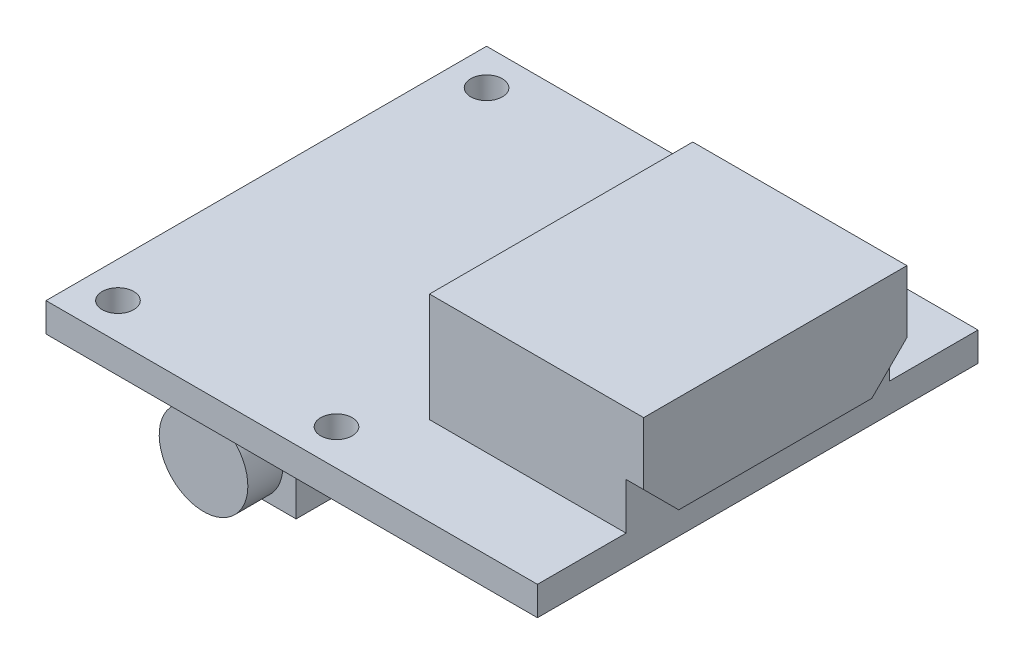
SolidWorks part; units mm, degrees
ref_plane "Front" through (0, 0, 0) normal (0, 0, 1) x (1, 0, 0)
ref_plane "Top" through (0, 0, 0) normal (0, 1, 0) x (1, 0, 0)
ref_plane "Right" through (0, 0, 0) normal (1, 0, 0) x (0, 0, -1)
sketch "Sketch1" plane through (0, 0, 0) normal (0, 1, 0) x (1, 0, 0)
  line L1 (-14, -12.55) -> (14, -12.55)
  line L2 (-14, -12.55) -> (-14, 12.55)
  line L3 (-14, 12.55) -> (14, 12.55)
  line L4 (14, -12.55) -> (14, 12.55)
  line L5 (-14, -12.55) -> (14, 12.55) construction
  line L6 (-14, 12.55) -> (14, -12.55) construction
  point P0 (0, 0)
  dimension "D1" = 28
  dimension "D2" = 25.1
extrude "Boss-Extrude1" add sketch "Sketch1" along normal blind 1.65
sketch "Sketch2" plane through (0, 1.65, 0) normal (0, 1, 0) x (1, 0, 0)
  line L0 (14, -12.55) -> (14, 12.55) construction
  line L1 (14, 7.5) -> (2.8, 7.5)
  line L2 (14, 7.5) -> (14, -7.5)
  line L3 (14, -7.5) -> (2.8, -7.5)
  line L4 (2.8, 7.5) -> (2.8, -7.5)
  point P6 (14, 0)
  dimension "D1" = 11.2
  dimension "D2" = 15
extrude "Boss-Extrude2" add sketch "Sketch2" along normal blind 6.2
sketch "Sketch3" plane through (14, 0, 0) normal (1, 0, 0) x (0, 0, -1)
  line L0 (-7.5, 4.3) -> (-7.5, 7.85)
  line L1 (-7.5, 7.85) -> (-7.5, 1.65) construction
  line L2 (-7.5, 7.85) -> (7.5, 7.85)
  line L3 (7.5, 7.85) -> (7.5, 4.3)
  line L4 (7.5, 7.85) -> (7.5, 1.65) construction
  line L5 (-7.5, 4.3) -> (-5.5, 2.3)
  line L6 (-5.5, 2.3) -> (5.5, 2.3)
  line L7 (5.5, 2.3) -> (7.5, 4.3)
  dimension "D1" = 5.55
  dimension "D2" = 11
  dimension "D3" = 45
extrude "Boss-Extrude3" add sketch "Sketch3" along normal blind 1
sketch "Sketch4" plane through (0, 0, 0) normal (0, -1, 0) x (1, 0, 0)
  line L0 (-14, -12.55) -> (-14, 12.55) construction
  line L1 (-8.8, 10.05) -> (-2.25, 10.05)
  line L2 (-8.8, 10.05) -> (-8.8, -1.9)
  line L3 (-8.8, -1.9) -> (-2.25, -1.9)
  line L4 (-2.25, 10.05) -> (-2.25, -1.9)
  line L5 (-14, 12.55) -> (14, 12.55) construction
  dimension "D1" = 5.2
  dimension "D2" = 6.55
  dimension "D3" = 11.95
  dimension "D4" = 2.5
extrude "Boss-Extrude4" add sketch "Sketch4" along normal blind 4.5
sketch "Sketch5" plane through (0, 0, 10.05) normal (0, 0, 1) x (1, 0, 0)
  line L0 (-8.8, -4.5) -> (-8.8, 0) construction
  line L1 (-2.25, -4.5) -> (-8.8, -4.5) construction
  circle A0 centre (-5.525, -2.25) radius 2.525
  point P5 (-8.8, -2.25)
  point P9 (-5.525, -4.5)
  dimension "D1" = 5.05
extrude "Boss-Extrude5" add sketch "Sketch5" along normal blind 2
sketch "Sketch6" plane through (0, 0, 0) normal (0, -1, 0) x (-1, 0, 0)
  line L0 (-0.5, -9.6) -> (-0.5, 9.6) construction
  line L1 (11.95, 10.5) -> (-0.5, 10.5) construction
  line L2 (11.95, 10.5) -> (11.95, -10.5) construction
  line L3 (11.95, -10.5) -> (-0.5, -10.5) construction
  line L4 (-0.5, 10.5) -> (-0.5, -10.5) construction
  line L5 (11.95, 10.5) -> (-0.5, -10.5) construction
  line L6 (11.95, -10.5) -> (-0.5, 10.5) construction
  line L7 (11.05, -10.5) -> (0.4, -10.5) construction
  line L8 (11.95, -10.5) -> (14, -10.5) construction
  line L9 (14, 12.55) -> (14, -12.55) construction
  line L10 (11.95, -10.5) -> (11.95, -12.55) construction
  line L11 (14, -12.55) -> (-14, -12.55) construction
  circle A0 centre (11.95, -10.5) radius 0.9
  circle A1 centre (11.95, 10.5) radius 0.9
  circle A2 centre (-0.5, 10.5) radius 0.9
  circle A3 centre (-0.5, -10.5) radius 0.9
  point P0 (5.725, 0)
  dimension "D1" = 1.8
  dimension "D2" = 10.65
  dimension "D3" = 19.2
extrude "Cut-Extrude1" cut sketch "Sketch6" against normal through all
